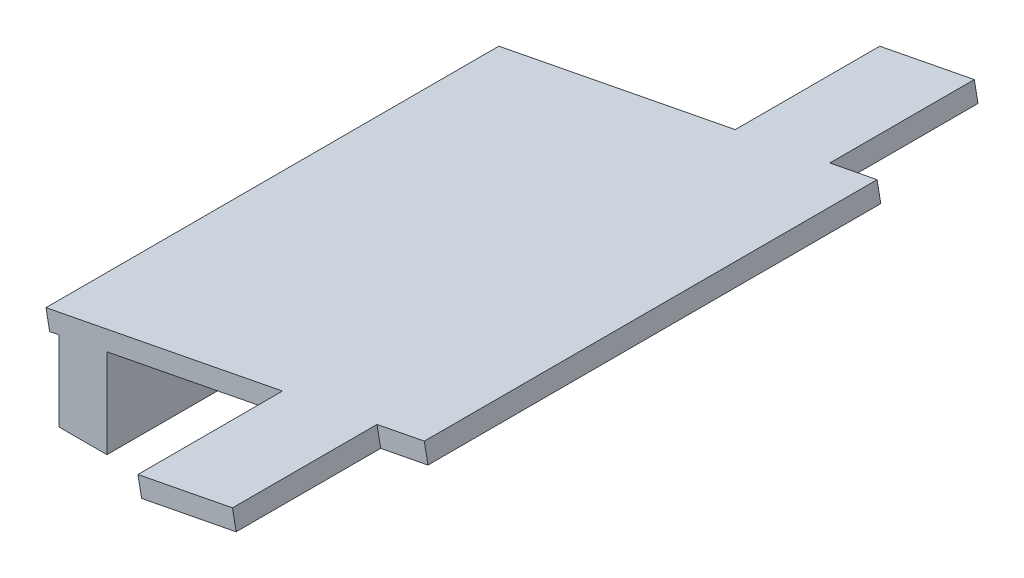
SolidWorks part; units mm, degrees
ref_plane "Front Plane" through (0, 0, 0) normal (0, 0, 1) x (1, 0, 0)
ref_plane "Top Plane" through (0, 0, 0) normal (0, 1, 0) x (1, 0, 0)
ref_plane "Right Plane" through (0, 0, 0) normal (1, 0, 0) x (0, 0, -1)
sketch "Sketch1" plane through (0, 0, 0) normal (0, 1, 0) x (1, 0, 0)
  line L1 (-12.2214, 22.7768) -> (27.7786, 22.7768)
  line L2 (-12.2214, 22.7768) -> (-12.2214, -24.2232)
  line L3 (-12.2214, -24.2232) -> (27.7786, -24.2232)
  line L4 (27.7786, 22.7768) -> (27.7786, -24.2232)
  line L6 (27.7786, 15.2768) -> (27.7786, 5.2768)
  dimension "D1" = 47
  dimension "D2" = 40
extrude "Boss-Extrude1" add sketch "Sketch1" along normal blind 2 contours L4 L3 L2 L1
move or copy body "Body-Move/Copy1" bodies to move or copy 101 copy no rotation origin (9.1144, 1.5, 0) rotation axis (0, 0, 1) rotation angle 11
sketch "Sketch2" plane through (0.3516, 0, 24.2232) normal (0, 0, 1) x (1, 0, 0)
  line L1 (-5.9479, -2.139) -> (-10.9479, -2.139)
  line L2 (-5.9479, -2.139) -> (-5.9479, -12.139)
  line L3 (-5.9479, -12.139) -> (-10.9479, -12.139)
  line L4 (-10.9479, -2.139) -> (-10.9479, -12.139)
  dimension "D1" = 10
  dimension "D2" = 5
extrude "Boss-Extrude2" add sketch "Sketch2" against normal blind 46.5
sketch "Sketch4" plane through (-0.0445, 0.229, 0) normal (-0.1908, 0.9816, 0) x (0.9816, 0.1908, 0)
  line L0 (-12.1026, -24.2232) -> (27.8974, -24.2232) construction
  line L1 (12.8974, -24.2232) -> (22.8974, -24.2232)
  line L2 (12.8974, -24.2232) -> (12.8974, -39.2232)
  line L3 (12.8974, -39.2232) -> (22.8974, -39.2232)
  line L4 (22.8974, -24.2232) -> (22.8974, -39.2232)
  line L5 (27.8974, 22.7768) -> (27.8974, -24.2232) construction
  dimension "D1" = 10
  dimension "D2" = 15
  dimension "D3" = 5
extrude "Boss-Extrude3" add sketch "Sketch4" against normal blind 2
sketch "Sketch5" plane through (-0.0445, 0.229, 0) normal (-0.1908, 0.9816, 0) x (0.9816, 0.1908, 0)
  line L0 (-12.1026, 22.7768) -> (27.8974, 22.7768) construction
  line L1 (12.8974, 37.7768) -> (22.8974, 37.7768)
  line L2 (12.8974, 37.7768) -> (12.8974, 22.7768)
  line L3 (12.8974, 22.7768) -> (22.8974, 22.7768)
  line L4 (22.8974, 37.7768) -> (22.8974, 22.7768)
  dimension "D1" = 15
  dimension "D2" = 10
  dimension "D3" = 5
extrude "Boss-Extrude4" add sketch "Sketch5" against normal blind 2
